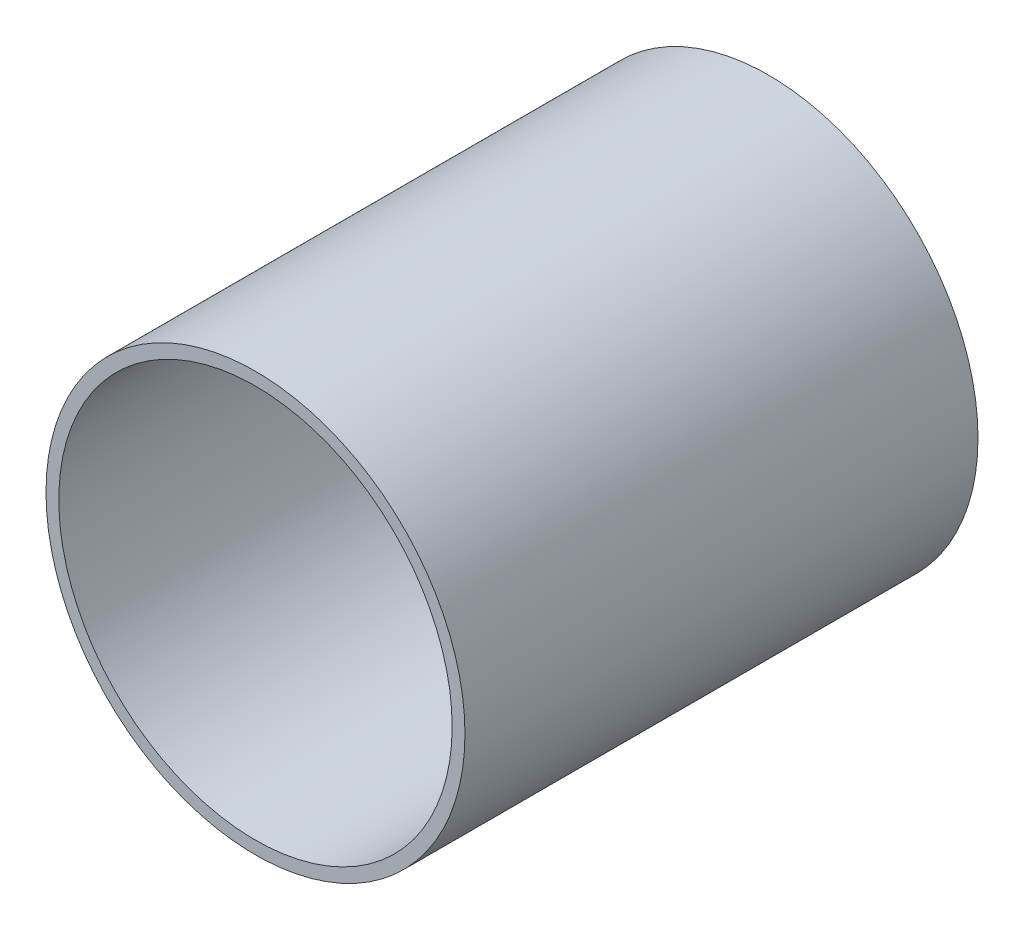
SolidWorks part; units mm, degrees
material "Plain Carbon Steel"
ref_plane "Front Plane" through (0, 0, 0) normal (0, 0, 1) x (1, 0, 0)
ref_plane "Top Plane" through (0, 0, 0) normal (0, 1, 0) x (1, 0, 0)
ref_plane "Right Plane" through (0, 0, 0) normal (1, 0, 0) x (0, 0, -1)
sketch "Sketch1" plane through (0, 0, 0) normal (0, 0, 1) x (1, 0, 0)
  circle A0 centre (0, 0) radius 2.45
  dimension "D1" = 4.9
extrude "Boss-Extrude1" add sketch "Sketch1" along normal blind 6
sketch "Sketch2" plane through (0, 0, 6) normal (0, 0, 1) x (1, 0, 0)
  circle A0 centre (0, 0) radius 2.3
  dimension "D1" = 4.6
extrude "Cut-Extrude1" cut sketch "Sketch2" against normal blind 5.75
sketch "Sketch3" plane through (0, 0, 0) normal (0, 1, 0) x (1, 0, 0)
  line L0 (0, 0) -> (0, -8.133) construction
